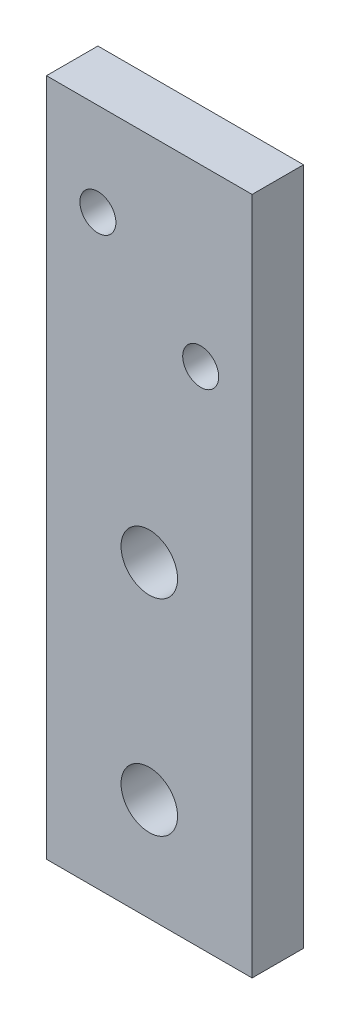
SolidWorks part; units mm, degrees
ref_plane "Plan de face" through (0, 0, 0) normal (0, 0, 1) x (1, 0, 0)
ref_plane "Plan de dessus" through (0, 0, 0) normal (0, 1, 0) x (1, 0, 0)
ref_plane "Plan de droite" through (0, 0, 0) normal (1, 0, 0) x (0, 0, -1)
sketch "Esquisse1" plane through (0, 0, 0) normal (0, 0, 1) x (1, 0, 0)
  line L0 (-11.1747, 15.8913) -> (-11.1747, 7.8913) construction
  line L1 (-16.1747, 24.8913) -> (3.8253, 24.8913)
  line L2 (-16.1747, 24.8913) -> (-16.1747, -41.1087)
  line L3 (-16.1747, -41.1087) -> (3.8253, -41.1087)
  line L4 (3.8253, 24.8913) -> (3.8253, -41.1087)
  line L5 (-11.1747, 7.8913) -> (-1.1747, 7.8913) construction
  line L6 (-16.1747, -1.1087) -> (3.8253, -1.1087) construction
  line L7 (2.5931, -1.1087) -> (2.5931, 24.8913) construction
  circle A0 centre (-6.1747, -31.1087) radius 2.75
  circle A1 centre (-6.1747, -11.1087) radius 2.75
  circle A2 centre (-11.1747, 15.8913) radius 1.75
  circle A3 centre (-1.1747, 7.8913) radius 1.75
  point P12 (-6.1747, 7.8913)
  point P13 (-6.1747, -41.1087)
  point P19 (2.5931, 11.8913)
  point P20 (-11.1747, 11.8913)
  dimension "D3" = 5.5
  dimension "D7" = 3.5
  dimension "D1" = 20
  dimension "D2" = 66
  dimension "D4" = 20
  dimension "D5" = 10
  dimension "D6" = 10
  dimension "D8" = 8
  dimension "D9" = 40
extrude "Boss.-Extru.1" add sketch "Esquisse1" along normal blind 5
